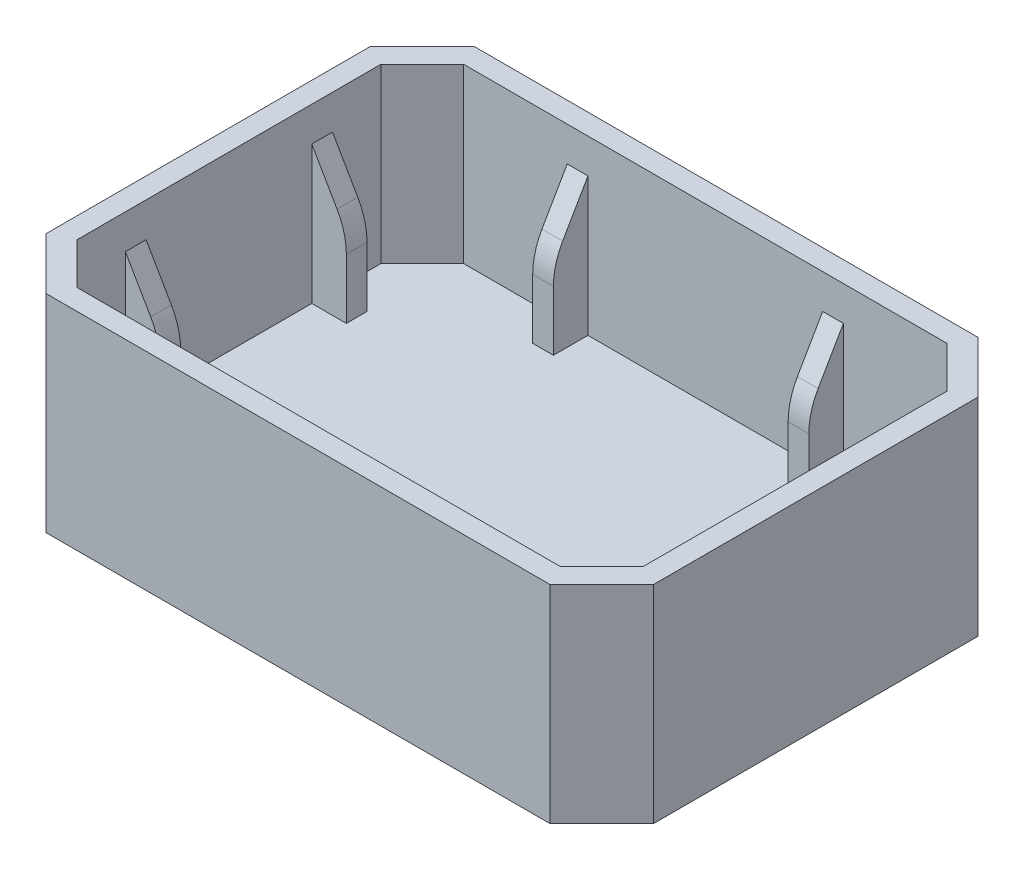
SolidWorks part; units mm, degrees
ref_plane "前视基准面" through (0, 0, 0) normal (0, 0, 1) x (1, 0, 0)
ref_plane "上视基准面" through (0, 0, 0) normal (0, 1, 0) x (1, 0, 0)
ref_plane "右视基准面" through (0, 0, 0) normal (1, 0, 0) x (0, 0, -1)
other "Configuration Table"
sketch "草图1" plane through (0, 0, 0) normal (0, 1, 0) x (1, 0, 0)
  line L1 (-36, -23) -> (36, -23)
  line L2 (-36, -23) -> (-36, 23)
  line L3 (-36, 23) -> (36, 23)
  line L4 (36, -23) -> (36, 23)
  line L5 (-36, -23) -> (36, 23) construction
  line L6 (-36, 23) -> (36, -23) construction
  point P0 (0, 0)
  dimension "D1" = 46
  dimension "D2" = 72
sketch "草图3" plane through (0, 0, 0) normal (0, 1, 0) x (1, 0, 0)
  line L5 (-44, -31) -> (44, -31)
  line L6 (44, -31) -> (44, 31)
  line L7 (44, 31) -> (-44, 31)
  line L8 (-44, 31) -> (-44, -31)
  line L9 (-36, -23) -> (36, -23)
  line L10 (36, -23) -> (36, 23)
  line L11 (36, 23) -> (-36, 23)
  line L12 (-36, 23) -> (-36, -23)
  line L13 (-36, -23) -> (36, -23) construction
  line L14 (36, -23) -> (36, 23) construction
  line L15 (36, 23) -> (-36, 23) construction
  line L16 (-36, 23) -> (-36, -23) construction
  dimension "D1" = 0
  dimension "D2" = 8
extrude "凸台-拉伸2" add sketch "草图3" along normal blind 30
shell "抽壳1" thickness 3
sketch "草图5" plane through (0, 0, 0) normal (0, 0, 1) x (1, 0, 0)
  line L1 (-41, 30) -> (-41, 5) construction
  line L2 (0, 0) -> (0, 30) construction
  line L3 (-41, 25) -> (-41, 5)
  line L4 (-41, 25) -> (-36, 16.3397)
  line L5 (-36, 16.3397) -> (-36, 5)
  line L6 (-36, 5) -> (-41, 5)
  line L7 (-44, 30) -> (44, 30) construction
  line L8 (36, 5) -> (41, 5)
  line L9 (36, 16.3397) -> (36, 5)
  line L10 (41, 25) -> (36, 16.3397)
  line L11 (41, 25) -> (41, 5)
  line L12 (-36, 0) -> (36, 0) construction
  line L13 (-36, 0) -> (36, 0) construction
  point P16 (0, 0)
  dimension "D1" = 20
  dimension "D3" = 30
extrude "凸台-拉伸3" add sketch "草图5" along normal mid plane 30
fillet "圆角1" radius 10 2 edges at (-36, 16.3397, 0) (36, 16.3397, 0)
sketch "草图6" plane through (0, 0, 0) normal (0, 0, 1) x (1, 0, 0)
  line L4 (36, 5) -> (41, 5)
  line L5 (41, 5) -> (41, 25)
  line L6 (41, 25) -> (36, 16.3397)
  line L7 (36, 16.3397) -> (36, 5)
  line L8 (36, 5) -> (41, 5)
  line L9 (41, 5) -> (41, 25)
  line L10 (41, 25) -> (36, 16.3397)
  line L11 (36, 16.3397) -> (36, 5)
  line L12 (-41, 25) -> (-41, 5)
  line L13 (-41, 5) -> (-36, 5)
  line L14 (-36, 5) -> (-36, 16.3397)
  line L15 (-36, 16.3397) -> (-41, 25)
  line L16 (-41, 25) -> (-41, 5)
  line L17 (-41, 5) -> (-36, 5)
  line L18 (-36, 5) -> (-36, 16.3397)
  line L19 (-36, 16.3397) -> (-41, 25)
  dimension "D1" = 0
  dimension "D2" = 0
extrude "切除-拉伸1" cut sketch "草图6" against normal mid plane 24
sketch "草图7" plane through (0, 0, 0) normal (1, 0, 0) x (0, 0, -1)
  line L0 (-28, 30) -> (-28, 5) construction
  line L2 (-28, 25) -> (-23, 16.3397)
  line L3 (-28, 25) -> (-28, 5)
  line L4 (-23, 16.3397) -> (-23, 5)
  line L5 (-23, 5) -> (-28, 5)
  line L6 (-23, 0) -> (23, 0) construction
  line L7 (-23, 0) -> (23, 0) construction
  line L8 (0, 0) -> (0, 30) construction
  line L9 (-31, 30) -> (31, 30) construction
  line L10 (23, 5) -> (28, 5)
  line L11 (23, 16.3397) -> (23, 5)
  line L12 (28, 25) -> (28, 5)
  line L13 (28, 25) -> (23, 16.3397)
  dimension "D1" = 30
  dimension "D2" = 20
extrude "凸台-拉伸4" add sketch "草图7" along normal mid plane 40
fillet "圆角2" radius 10 2 edges at (0, 16.3397, 23) (0, 16.3397, -23)
sketch "草图8" plane through (0, 0, 0) normal (1, 0, 0) x (0, 0, -1)
  line L4 (23, 5) -> (28, 5)
  line L5 (28, 5) -> (28, 25)
  line L6 (28, 25) -> (23, 16.3397)
  line L7 (23, 16.3397) -> (23, 5)
  line L8 (23, 5) -> (28, 5)
  line L9 (28, 5) -> (28, 25)
  line L10 (28, 25) -> (23, 16.3397)
  line L11 (23, 16.3397) -> (23, 5)
  line L12 (-23, 16.3397) -> (-28, 25)
  line L13 (-23, 5) -> (-23, 16.3397)
  line L14 (-28, 5) -> (-23, 5)
  line L15 (-28, 25) -> (-28, 5)
  line L16 (-23, 16.3397) -> (-28, 25)
  line L17 (-23, 5) -> (-23, 16.3397)
  line L18 (-28, 5) -> (-23, 5)
  line L19 (-28, 25) -> (-28, 5)
  dimension "D1" = 0
  dimension "D2" = 0
extrude "切除-拉伸2" cut sketch "草图8" against normal mid plane 34
chamfer "倒角1" distance 6 angle 45 4 edges at (-41, 17.5, -28) (-41, 17.5, 28) (41, 17.5, 28) (41, 17.5, -28)
chamfer "倒角2" distance 7.5 angle 45 4 edges at (-44, 15, -31) (44, 15, -31) (44, 15, 31) (-44, 15, 31)
